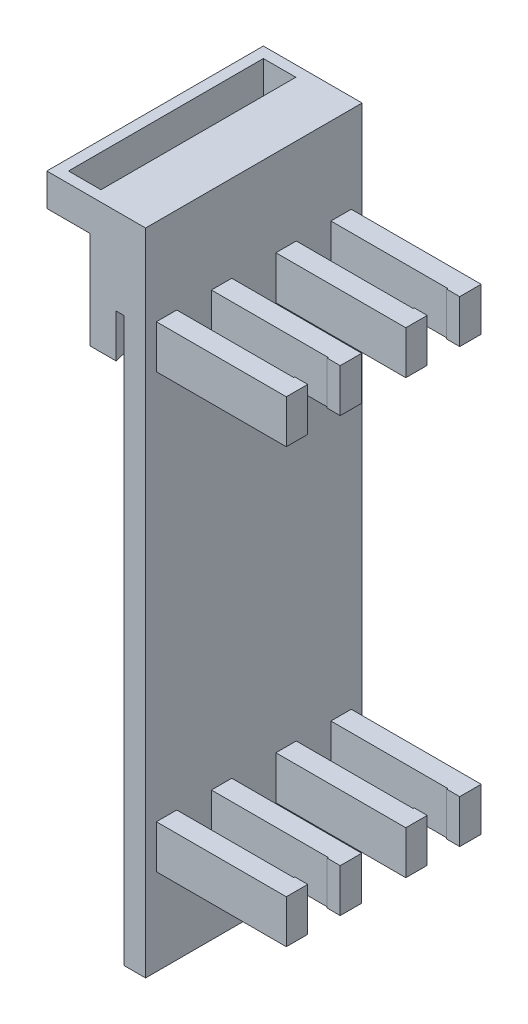
SolidWorks part; units mm, degrees
ref_plane "Front Plane" through (0, 0, 0) normal (0, 0, 1) x (1, 0, 0)
ref_plane "Top Plane" through (0, 0, 0) normal (0, 1, 0) x (1, 0, 0)
ref_plane "Right Plane" through (0, 0, 0) normal (1, 0, 0) x (0, 0, -1)
sketch "Sketch1" plane through (0, 0, 0) normal (0, 0, 1) x (1, 0, 0)
  line L0 (0, 0) -> (0, 30)
  line L1 (0, 30) -> (12.8, 30)
  line L2 (12.8, 30) -> (12.8, 0)
  line L3 (12.8, 0) -> (7.8, 0)
  line L4 (7.8, 0) -> (7.8, 10)
  line L5 (7.8, 10) -> (6, 10)
  line L6 (6, 10) -> (6, 0)
  line L7 (6, 0) -> (0, 0)
  dimension "D1" = 1.8
  dimension "D2" = 6
  dimension "D3" = 5
  dimension "D4" = 30
  dimension "D5" = 10
extrude "Boss-Extrude1" add sketch "Sketch1" along normal blind 50
sketch "Sketch2" plane through (12.8, 0, 0) normal (1, 0, 0) x (0, 0, -1)
  line L0 (-50, 0) -> (-50, 30) construction
  line L1 (-47.5, 10) -> (-42.8, 10)
  line L2 (-47.5, 10) -> (-47.5, 0)
  line L3 (-47.5, 0) -> (-42.8, 0)
  line L4 (-42.8, 10) -> (-42.8, 0)
  line L5 (-34.8, 10) -> (-30.1, 10)
  line L6 (-34.8, 10) -> (-34.8, 0)
  line L7 (-34.8, 0) -> (-30.1, 0)
  line L8 (-30.1, 10) -> (-30.1, 0)
  line L17 (-50, 0) -> (0, 0) construction
  dimension "D1" = 4.7
  dimension "D2" = 10
  dimension "D3" = 8
  dimension "D5" = 2.5
  dimension "D6" = 0
extrude "Boss-Extrude2" add sketch "Sketch2" along normal blind 30
sketch "Sketch3" plane through (0, 0, 0) normal (0, -1, 0) x (1, 0, 0)
  line L0 (7.8, 50) -> (12.8, 50)
  line L1 (12.8, 50) -> (12.8, 0)
  line L2 (12.8, 0) -> (7.8, 0)
  line L3 (7.8, 0) -> (7.8, 50)
extrude "Boss-Extrude3" add sketch "Sketch3" along normal blind 120
sketch "Sketch4" plane through (0, 0, 42.8) normal (0, 0, -1) x (-1, 0, 0)
  line L0 (-42.8, 10) -> (-39.8, 10)
  line L1 (-42.8, 10) -> (-12.8, 10) construction
  line L2 (-39.8, 10) -> (-39.8, 0)
  line L3 (-42.8, 0) -> (-12.8, 0) construction
  line L4 (-39.8, 0) -> (-42.8, 0)
  line L5 (-42.8, 0) -> (-42.8, 10)
  dimension "D1" = 3
extrude "Boss-Extrude4" add sketch "Sketch4" along normal blind 0.25
sketch "Sketch5" plane through (0, 0, 34.8) normal (0, 0, 1) x (1, 0, 0)
  line L0 (42.8, 10) -> (39.8, 10)
  line L1 (42.8, 10) -> (12.8, 10) construction
  line L2 (39.8, 10) -> (39.8, 0)
  line L3 (42.8, 0) -> (12.8, 0) construction
  line L4 (39.8, 0) -> (42.8, 0)
  line L5 (42.8, 0) -> (42.8, 10)
  dimension "D1" = 3
extrude "Boss-Extrude5" add sketch "Sketch5" along normal blind 0.25
pattern_linear "LPattern1" count 2 spacing 27.6 along (0, 0, -1) of "Boss-Extrude2", "Boss-Extrude4", "Boss-Extrude5"
pattern_linear "LPattern2" count 2 spacing 100 along (0, -1, 0) of "Boss-Extrude2", "Boss-Extrude4", "Boss-Extrude5", "LPattern1"
sketch "Esboço2" plane through (0, 0, 0) normal (0, -1, 0) x (1, 0, 0)
  line L0 (6, 50) -> (6, 0)
  arc A0 (6, 50) -> (6, 0) centre (99.3089, 25) ccw
  dimension "D1" = 96.6
extrude "Corte-extrusão1" cut sketch "Esboço2" against normal blind 10
sketch "Esboço3" plane through (0, 0, 0) normal (-1, 0, 0) x (0, 0, 1)
  line L0 (50, 30) -> (50, 0) construction
  line L1 (0, 30) -> (50, 30)
  line L2 (0, 30) -> (0, 22.5)
  line L3 (0, 22.5) -> (50, 22.5)
  line L4 (50, 30) -> (50, 22.5)
  dimension "D1" = 7.5
extrude "Ressalto-extrusão2" add sketch "Esboço3" along normal blind 10
sketch "Esboço4" plane through (0, 22.5, 0) normal (0, -1, 0) x (1, 0, 0)
  line L0 (0, 0) -> (0, 50) construction
  line L1 (0, 47.5) -> (-7.5, 47.5)
  line L2 (0, 47.5) -> (0, 2.5)
  line L3 (0, 2.5) -> (-7.5, 2.5)
  line L4 (-7.5, 47.5) -> (-7.5, 2.5)
  line L5 (-10, 50) -> (0, 50) construction
  line L6 (-10, 0) -> (0, 0) construction
  dimension "D1" = 7.5
  dimension "D2" = 2.5
  dimension "D3" = 2.5
extrude "Corte-extrusão2" cut sketch "Esboço4" against normal blind 10
